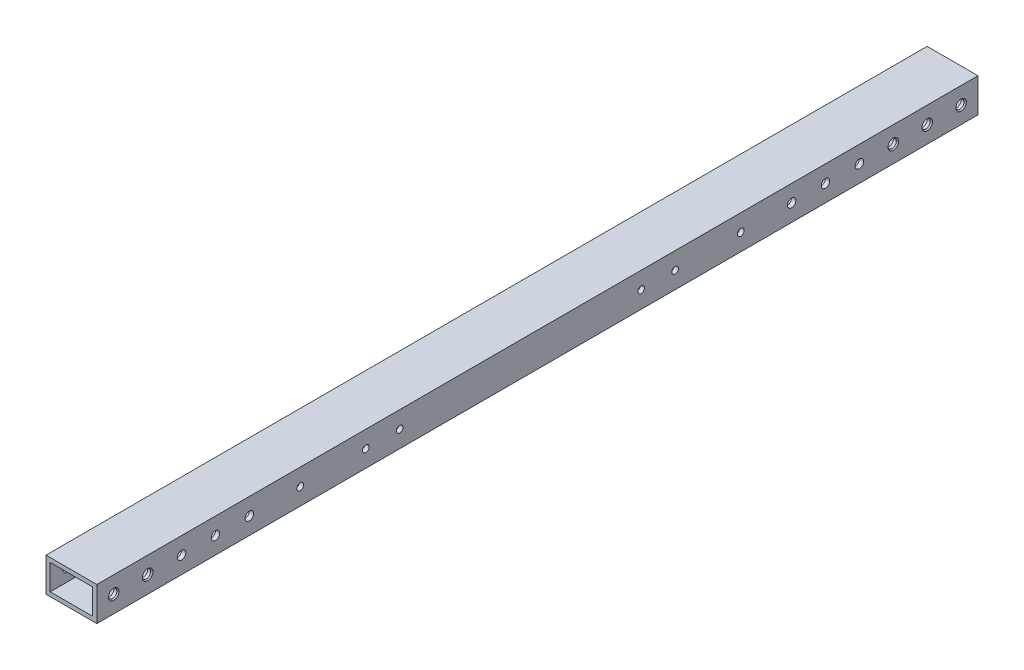
SolidWorks part; units mm, degrees
ref_plane "Front Plane" through (0, 0, 0) normal (0, 0, 1) x (1, 0, 0)
ref_plane "Top Plane" through (0, 0, 0) normal (0, 1, 0) x (1, 0, 0)
ref_plane "Right Plane" through (0, 0, 0) normal (1, 0, 0) x (0, 0, -1)
sketch "Sketch1" plane through (0, 0, 0) normal (0, 0, 1) x (1, 0, 0)
  line L0 (-15.875, 9.525) -> (15.875, 9.525)
  line L2 (-19.05, 12.7) -> (19.05, 12.7)
  line L3 (-19.05, 12.7) -> (-19.05, -12.7)
  line L4 (-19.05, -12.7) -> (19.05, -12.7)
  line L5 (19.05, 12.7) -> (19.05, -12.7)
  line L10 (15.875, 9.525) -> (15.875, -9.525)
  line L11 (-15.875, -9.525) -> (15.875, -9.525)
  line L12 (-15.875, 9.525) -> (-15.875, -9.525)
  point P12 (0, 12.7)
  point P14 (19.05, 0)
  dimension "Wall Thickness" = 3.175
  dimension "Outside Width" = 38.1
  dimension "Outside Height" = 25.4
  dimension "Inside Height" = 19.05
  dimension "Inside Width" = 31.75
sketch "Sketch2" plane through (0, 0, 0) normal (1, 0, 0) x (0, 0, -1)
  line L0 (330.2, 0) -> (-330.2, 0)
  point P4 (0, 0)
  point P7 (-330.2, 0)
  point P10 (330.2, 0)
  dimension "Length" = 660.4
sketch "Sketch3" plane through (0, 0, 0) normal (0, 0, 1) x (1, 0, 0)
  line L21 (19.05, 12.7) -> (-19.05, 12.7)
  line L22 (19.05, -12.7) -> (19.05, 12.7)
  line L23 (-19.05, -12.7) -> (19.05, -12.7)
  line L24 (-19.05, 12.7) -> (-19.05, -12.7)
  line L25 (19.05, 12.7) -> (-19.05, 12.7)
  line L26 (19.05, -12.7) -> (19.05, 12.7)
  line L27 (-19.05, -12.7) -> (19.05, -12.7)
  line L28 (-19.05, 12.7) -> (-19.05, -12.7)
  line L29 (15.875, 9.525) -> (-15.875, 9.525)
  line L30 (15.875, -9.525) -> (15.875, 9.525)
  line L31 (-15.875, -9.525) -> (15.875, -9.525)
  line L32 (-15.875, 9.525) -> (-15.875, -9.525)
  line L33 (15.875, 9.525) -> (-15.875, 9.525)
  line L34 (15.875, -9.525) -> (15.875, 9.525)
  line L35 (-15.875, -9.525) -> (15.875, -9.525)
  line L36 (-15.875, 9.525) -> (-15.875, -9.525)
  dimension "D1" = 0
  dimension "D2" = 0
extrude "Boss-Extrude1" add sketch "Sketch3" along normal up to vertex (330.2 mm away) and the other way up to vertex (330.2 mm away) up to point (0, 0, 330.2) other way up to point (0, 0, -330.2)
sketch "Drawing Reference" plane through (0, 0, 0) normal (1, 0, 0) x (0, 0, -1)
  line L0 (-330.2, 0) -> (330.2, 0) construction
  line L1 (0, -12.7) -> (0, 12.7) construction
  line L2 (-330.2, -12.7) -> (330.2, -12.7) construction
  line L5 (-330.2, 12.7) -> (330.2, 12.7) construction
  point P7 (-302.768, 0)
  point P8 (302.768, 0)
  dimension "D1" = 27.432
sketch "Sketch4" plane through (-19.05, 0, 0) normal (-1, 0, 0) x (0, 0, 1)
  line L0 (-330.2, 0) -> (-317.5, 0)
  line L1 (-330.2, 12.7) -> (-330.2, -12.7) construction
  line L2 (-317.5, 0) -> (-292.1, 0)
  line L3 (-292.1, 0) -> (-266.7, 0)
  line L4 (-266.7, 0) -> (-241.3, 0)
  line L5 (-241.3, 0) -> (-215.9, 0)
  line L6 (-215.9, 0) -> (-190.5, 0)
  line L7 (330.2, 0) -> (317.5, 0)
  line L8 (330.2, 12.7) -> (330.2, -12.7) construction
  line L9 (317.5, 0) -> (292.1, 0)
  line L10 (292.1, 0) -> (266.7, 0)
  line L11 (266.7, 0) -> (241.3, 0)
  line L12 (241.3, 0) -> (215.9, 0)
  line L13 (332.74, -88.9001) -> (353.06, -88.9001) construction
hole_wizard "1/4 (0.25) Diameter Hole2" positions "Sketch7" profile "Sketch8" hole size "1/4" standard "ANSI Inch" end condition through all
sketch "Sketch7" plane through (-19.05, 0, 0) normal (-1, 0, 0) x (0, 0, 1)
  point P0 (-317.5, 0)
  point P3 (-292.1, 0)
  point P7 (317.5, 0)
  point P11 (-266.7, 0)
  point P14 (292.1, 0)
sketch "Sketch8" plane through (-19.05, 0, -317.5) normal (0, 1, 0) x (0, 0, 1)
  line L0 (0, 0) -> (0, 38.1)
  line L1 (0, 38.1) -> (3.9624, 38.1)
  line L2 (3.175, 37.1942) -> (3.175, 0)
  line L5 (3.175, 0) -> (0, 0)
  line L7 (3.9624, 38.1) -> (3.175, 37.1942)
  line L8 (-3.9624, 38.1) -> (-3.175, 37.1942) construction
  line L11 (0, -6.35) -> (0, 107.95) construction
  dimension "Thru Hole Dia." = 6.35
  dimension "Thru Hole Depth" = 38.1
  dimension "Far C'Sink Dia." = 7.9248
  dimension "Far C'Sink Angle" = 82
hole_wizard "1/4 (0.25) Diameter Hole3" positions "Sketch9" profile "Sketch10" hole size "1/4" standard "ANSI Inch" end condition through all
sketch "Sketch9" plane through (19.05, 0, 0) normal (1, 0, 0) x (0, 0, -1)
  point P0 (-266.7, 0)
  point P3 (-241.3, 0)
  point P6 (-215.9, 0)
  point P9 (241.3, 0)
  point P12 (215.9, 0)
  point P15 (190.5, 0)
sketch "Sketch10" plane through (19.05, 0, 266.7) normal (0, 1, 0) x (0, 0, -1)
  line L0 (0, 0) -> (0, 38.1)
  line L1 (0, 38.1) -> (3.175, 38.1)
  line L2 (3.175, 38.1) -> (3.175, 0)
  line L5 (3.175, 0) -> (0, 0)
  line L11 (0, -6.35) -> (0, 107.95) construction
  dimension "Thru Hole Dia." = 6.35
  dimension "Thru Hole Depth" = 38.1
hole_wizard "13/64 (0.20313) Diameter Hole1" positions "Sketch11" profile "Sketch12" hole size "13/64" standard "ANSI Inch" end condition through all
sketch "Sketch11" plane through (19.05, 0, 0) normal (1, 0, 0) x (0, 0, -1)
  point P0 (152.4, 0)
  point P3 (-177.8, 0)
sketch "Sketch12" plane through (19.05, 0, -152.4) normal (0, 1, 0) x (0, 0, -1)
  line L0 (0, 0) -> (0, 38.1)
  line L1 (0, 38.1) -> (2.5798, 38.1)
  line L2 (2.5798, 38.1) -> (2.5798, 0)
  line L5 (2.5798, 0) -> (0, 0)
  line L11 (0, -6.35) -> (0, 107.95) construction
  dimension "Thru Hole Dia." = 5.1595
  dimension "Thru Hole Depth" = 38.1
sketch "Sketch13" plane through (19.05, 0, 0) normal (1, 0, 0) x (0, 0, -1)
  line L0 (-103.1875, 0) -> (-128.5875, 0)
  line L1 (77.7875, 0) -> (103.1875, 0)
hole_wizard "#10 Clearance Hole1" positions "Sketch14" profile "Sketch15" hole size "#10" standard "ANSI Inch" end condition through all
sketch "Sketch14" plane through (19.05, 0, 0) normal (1, 0, 0) x (0, 0, -1)
  point P0 (-128.5875, 0)
  point P3 (-103.1875, 0)
  point P7 (77.7875, 0)
  point P10 (103.1875, 0)
sketch "Sketch15" plane through (19.05, 0, 128.5875) normal (0, 1, 0) x (0, 0, -1)
  line L0 (0, 0) -> (0, 38.1)
  line L1 (0, 38.1) -> (2.4892, 38.1)
  line L2 (2.4892, 38.1) -> (2.4892, 0)
  line L5 (2.4892, 0) -> (0, 0)
  line L11 (0, -6.35) -> (0, 107.95) construction
  dimension "Thru Hole Dia." = 4.9784
  dimension "Thru Hole Depth" = 38.1
equation "\"D1@Drawing Reference\"=\"Outside Width@Sketch1\" * 0.72"
